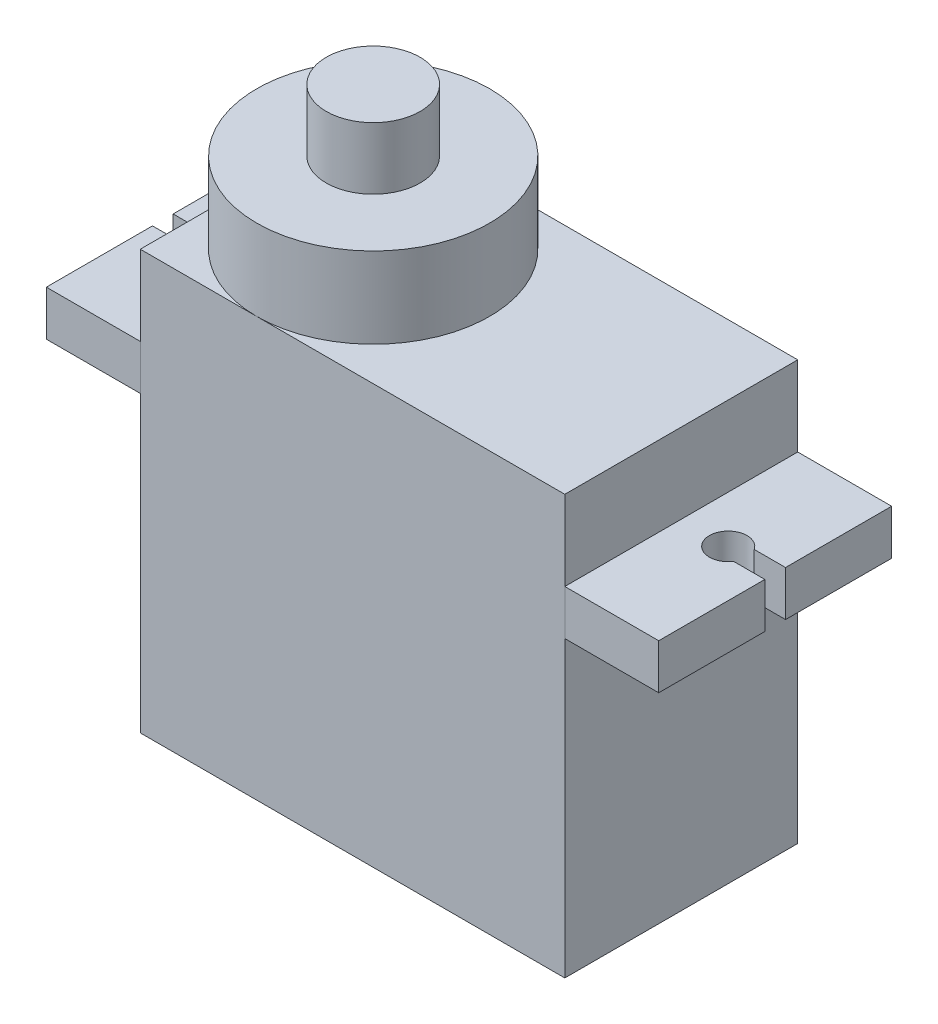
SolidWorks part; units mm, degrees
ref_plane "前视基准面" through (0, 0, 0) normal (0, 0, 1) x (1, 0, 0)
ref_plane "上视基准面" through (0, 0, 0) normal (0, 1, 0) x (1, 0, 0)
ref_plane "右视基准面" through (0, 0, 0) normal (1, 0, 0) x (0, 0, -1)
sketch "草图1" plane through (0, 0, 0) normal (0, 1, 0) x (1, 0, 0)
  line L1 (-11.3, 6.2) -> (11.3, 6.2)
  line L2 (-11.3, 6.2) -> (-11.3, -6.2)
  line L3 (-11.3, -6.2) -> (11.3, -6.2)
  line L4 (11.3, 6.2) -> (11.3, -6.2)
  line L5 (0, -6.2) -> (0, 6.2) construction
  line L6 (-11.3, 0) -> (11.3, 0) construction
  point P0 (0, 0)
  dimension "D1" = 22.6
  dimension "D2" = 12.4
extrude "凸台-拉伸1" add sketch "草图1" along normal blind 22.3
sketch "草图2" plane through (0, 0, 6.2) normal (0, 0, 1) x (1, 0, 0)
  line L0 (11.3, 22.3) -> (11.3, 0) construction
  line L1 (11.3, 18.05) -> (16.3, 18.05)
  line L2 (11.3, 18.05) -> (11.3, 15.65)
  line L3 (11.3, 15.65) -> (16.3, 15.65)
  line L4 (16.3, 18.05) -> (16.3, 15.65)
  line L5 (-11.3, 22.3) -> (11.3, 22.3) construction
  line L6 (0, 0) -> (0, 13.1092) construction
  line L7 (-11.3, 15.65) -> (-16.3, 15.65)
  line L8 (-16.3, 18.05) -> (-16.3, 15.65)
  line L9 (-11.3, 18.05) -> (-16.3, 18.05)
  line L10 (-11.3, 18.05) -> (-11.3, 15.65)
  dimension "D1" = 4.25
  dimension "D2" = 2.4
  dimension "D3" = 5
extrude "凸台-拉伸2" add sketch "草图2" against normal through all separate body
sketch "草图3" plane through (0, 18.05, 0) normal (0, 1, 0) x (1, 0, 0)
  line L0 (14.6352, 0.55) -> (16.3, 0.55)
  line L1 (16.3, 6.2) -> (16.3, -6.2) construction
  line L2 (16.3, 0.55) -> (16.3, -0.55)
  line L3 (16.3, -0.55) -> (14.6352, -0.55)
  line L4 (0, 0) -> (13.8, 0) construction
  line L5 (0, 0) -> (0, 7.8737) construction
  line L12 (-14.6352, -0.55) -> (-16.3, -0.55)
  line L13 (-16.3, 0.55) -> (-14.6352, 0.55)
  line L19 (-16.3, 0.55) -> (-16.3, -0.55)
  arc A0 (14.6352, 0.55) -> (14.6352, -0.55) centre (13.8, 0) ccw
  arc A1 (-14.6352, 0.55) -> (-14.6352, -0.55) centre (-13.8, 0) cw
  dimension "D1" = 2
  dimension "D2" = 2.5
  dimension "D3" = 1.1
extrude "切除-拉伸1" cut sketch "草图3" against normal through all
sketch "草图4" plane through (0, 22.3, 0) normal (0, 1, 0) x (1, 0, 0)
  line L1 (-11.3, 6.2) -> (-11.3, -6.2) construction
  circle A0 centre (-5.1, 0) radius 6.2
  dimension "D1" = 12.4
extrude "凸台-拉伸3" add sketch "草图4" along normal blind 4.3
sketch "草图5" plane through (0, 26.6, 0) normal (0, 1, 0) x (1, 0, 0)
  circle A0 centre (-5.1, 0) radius 2.5
  dimension "D1" = 5
extrude "凸台-拉伸4" add sketch "草图5" along normal blind 3.3
